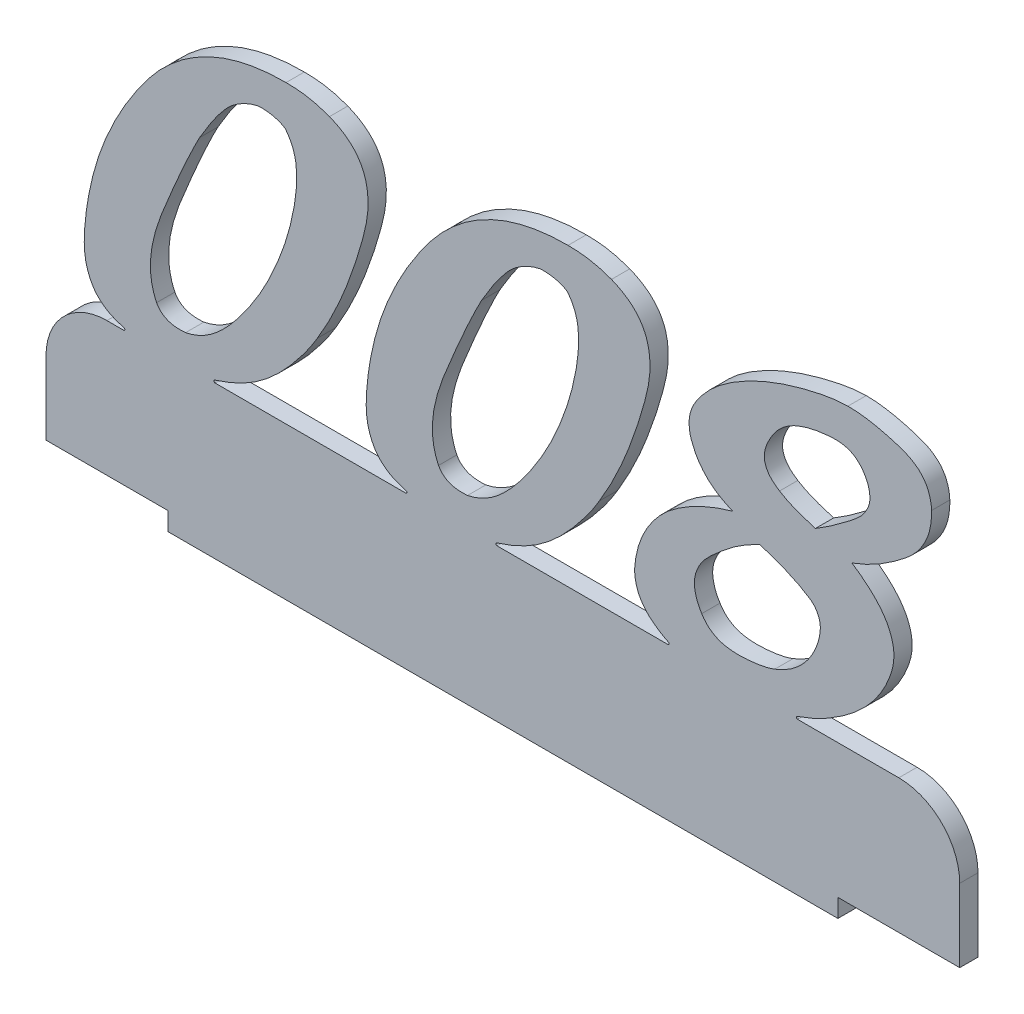
SolidWorks part; units mm, degrees
ref_plane "Front Plane" through (0, 0, 0) normal (0, 0, 1) x (1, 0, 0)
ref_plane "Top Plane" through (0, 0, 0) normal (0, 1, 0) x (1, 0, 0)
ref_plane "Right Plane" through (0, 0, 0) normal (1, 0, 0) x (0, 0, -1)
sketch "Sketch1" plane through (0, 0, 0) normal (0, 0, 1) x (1, 0, 0)
  line L0 (0, 20) -> (150, 20) construction
  line L1 (122.1085, 22) -> (150, 22)
  line L2 (0, 22) -> (0, 0)
  line L3 (0, 0) -> (20, 0)
  line L4 (150, 22) -> (150, 0)
  line L5 (0, 22) -> (14.4385, 22)
  line L6 (26.3356, 22) -> (60.7247, 22)
  line L7 (72.6217, 22) -> (103.0452, 22)
  line L11 (130, 0) -> (150, 0)
  line L13 (20, 0) -> (20, -3)
  line L14 (20, -3) -> (130, -3)
  line L15 (130, 0) -> (130, -3)
  spline S0 degree 3 poles (39.2717, 63.9355) (38.6705, 64.345) (37.2052, 64.8511) (35.6674, 64.9784) (34.8542, 64.9323) knots 0 0 0 0 0.469699 1 1 1 1
  spline S1 degree 3 poles (34.8542, 64.9323) (33.7095, 64.6916) (32.0915, 64.0141) (30.2031, 62.6365) (27.8952, 60.0585) (26.3615, 57.6069) (25.2178, 55.6282) knots 0 0 0 0 0.25259 0.375811 0.50377 1 1 1 1
  spline S2 degree 3 poles (25.2178, 55.6282) (24.7615, 54.8301) (24.1633, 53.5136) (23.2718, 51.6945) (22.5583, 50.113) (21.7939, 48.3937) (20.9934, 46.527) (20.1368, 44.5308) (19.2648, 42.4425) (18.4718, 40.3443) (17.8401, 38.3169) (17.3993, 36.4098) (17.1564, 34.6168) (17.1091, 32.9375) (17.3108, 30.9118) (17.7303, 29.4882) (18.1615, 28.6344) knots 0 0 0 0 0.095871 0.150957 0.21155 0.277044 0.347448 0.42366 0.503899 0.583776 0.657815 0.725493 0.787949 0.846481 0.90051 1 1 1 1
  spline S3 degree 3 poles (18.1615, 28.6344) (18.5199, 27.8914) (20.0194, 26.6841) (21.9323, 26.6676) (22.9113, 26.7384) knots 0 0 0 0 0.446154 1 1 1 1
  spline S4 degree 3 poles (22.9113, 26.7384) (24.3688, 27.0128) (26.5254, 28.0312) (29.0577, 30.199) (31.0082, 32.3562) (32.875, 34.8417) (34.6365, 37.5157) (36.227, 40.3422) (37.6215, 43.2984) (38.8196, 46.3154) (39.8112, 49.3275) (40.5299, 52.316) (41.0344, 55.2066) (41.204, 57.9083) (41.0021, 60.9389) (40.1273, 62.9274) (39.2717, 63.9355) knots 0 0 0 0 0.099523 0.157976 0.224341 0.295662 0.367825 0.440561 0.514606 0.588508 0.65979 0.72866 0.796042 0.857776 0.911265 1 1 1 1
  spline S5 degree 3 poles (14.4385, 22) (13.6581, 22.1621) (12.356, 22.4906) (10.6008, 23.1088) (9.2944, 23.9587) (8.1844, 24.9777) (7.3545, 26.255) (6.749, 27.7265) (6.1954, 30.0914) (6.2651, 32.0111) (6.3554, 33.3256) knots 0.412238 0.412238 0.412238 0.412238 0.501388 0.5623 0.61932 0.674488 0.729675 0.788153 0.851799 1 1 1 1
  spline S6 degree 3 poles (6.3554, 33.3256) (6.5223, 35.5537) (7.0115, 38.8793) (8.1409, 43.2161) (9.2037, 46.4254) (10.5584, 49.5588) (12.0964, 52.6646) (13.9041, 55.7078) (15.9112, 58.6749) (18.1087, 61.4642) (20.583, 63.8831) (23.2252, 65.9707) (26.1055, 67.6181) (29.141, 68.9659) (33.5634, 70.1882) (37.0421, 70.573) (39.4086, 70.5422) knots 0 0 0 0 0.122246 0.183381 0.245051 0.307032 0.370011 0.434579 0.500535 0.565958 0.62848 0.689454 0.749684 0.809559 0.870725 1 1 1 1
  spline S7 degree 3 poles (39.4086, 70.5422) (40.6688, 70.5317) (43.1116, 70.3882) (45.4518, 69.6784) (46.543, 69.2717) knots 0 0 0 0 0.519885 1 1 1 1
  spline S8 degree 3 poles (46.543, 69.2717) (47.8106, 68.7564) (49.6056, 67.763) (51.345, 65.7801) (52.2545, 64.1066) (52.7698, 62.2017) (52.9351, 60.0847) (52.742, 57.7539) (51.9926, 54.4145) (50.714, 50.2481) (48.4129, 43.9445) (46.2159, 39.5182) (44.5493, 36.7658) knots 0 0 0 0 0.111906 0.162582 0.212593 0.265416 0.321766 0.384451 0.454781 0.599581 0.738515 1 1 1 1
  spline S9 degree 3 poles (44.5493, 36.7658) (43.4578, 34.9086) (41.5875, 32.3381) (38.8382, 29.2151) (36.6695, 27.1459) (34.287, 25.3382) (31.6073, 23.8424) (28.9263, 22.7525) (27.1241, 22.2086) (26.3356, 22) knots 0 0 0 0 0.25786 0.380114 0.498337 0.616577 0.737567 0.865048 0.962803 0.962803 0.962803 0.962803
  spline S10 degree 3 poles (85.5579, 63.9355) (84.9566, 64.345) (83.4914, 64.8511) (81.9536, 64.9784) (81.1404, 64.9323) knots 0 0 0 0 0.469699 1 1 1 1
  spline S11 degree 3 poles (81.1404, 64.9323) (79.9957, 64.6916) (78.3776, 64.0141) (76.4893, 62.6365) (74.1814, 60.0585) (72.6477, 57.6069) (71.504, 55.6282) knots 0 0 0 0 0.25259 0.375811 0.50377 1 1 1 1
  spline S12 degree 3 poles (71.504, 55.6282) (71.0477, 54.8301) (70.4495, 53.5136) (69.5579, 51.6945) (68.8445, 50.113) (68.0801, 48.3937) (67.2796, 46.527) (66.423, 44.5308) (65.5509, 42.4425) (64.758, 40.3443) (64.1263, 38.3169) (63.6855, 36.4098) (63.4426, 34.6168) (63.3953, 32.9375) (63.597, 30.9118) (64.0165, 29.4882) (64.4477, 28.6344) knots 0 0 0 0 0.095871 0.150957 0.21155 0.277044 0.347448 0.42366 0.503899 0.583776 0.657815 0.725493 0.787949 0.846481 0.90051 1 1 1 1
  spline S13 degree 3 poles (64.4477, 28.6344) (64.8061, 27.8914) (66.3056, 26.6841) (68.2185, 26.6676) (69.1975, 26.7384) knots 0 0 0 0 0.446154 1 1 1 1
  spline S14 degree 3 poles (69.1975, 26.7384) (70.655, 27.0128) (72.8116, 28.0312) (75.3439, 30.199) (77.2943, 32.3562) (79.1611, 34.8417) (80.9227, 37.5157) (82.5131, 40.3422) (83.9076, 43.2984) (85.1058, 46.3154) (86.0973, 49.3275) (86.816, 52.316) (87.3206, 55.2066) (87.4902, 57.9083) (87.2883, 60.9389) (86.4135, 62.9274) (85.5579, 63.9355) knots 0 0 0 0 0.099523 0.157976 0.224341 0.295662 0.367825 0.440561 0.514606 0.588508 0.65979 0.72866 0.796042 0.857776 0.911265 1 1 1 1
  spline S15 degree 3 poles (60.7247, 22) (59.9443, 22.1621) (58.6422, 22.4906) (56.8869, 23.1088) (55.5805, 23.9587) (54.4706, 24.9777) (53.6407, 26.255) (53.0352, 27.7265) (52.4816, 30.0914) (52.5512, 32.0111) (52.6416, 33.3256) knots 0.412238 0.412238 0.412238 0.412238 0.501388 0.5623 0.61932 0.674488 0.729675 0.788153 0.851799 1 1 1 1
  spline S16 degree 3 poles (52.6416, 33.3256) (52.8085, 35.5537) (53.2977, 38.8793) (54.4271, 43.2161) (55.4899, 46.4254) (56.8445, 49.5588) (58.3825, 52.6646) (60.1903, 55.7078) (62.1973, 58.6749) (64.3949, 61.4642) (66.8691, 63.8831) (69.5114, 65.9707) (72.3916, 67.6181) (75.4271, 68.9659) (79.8495, 70.1882) (83.3282, 70.573) (85.6947, 70.5422) knots 0 0 0 0 0.122246 0.183381 0.245051 0.307032 0.370011 0.434579 0.500535 0.565958 0.62848 0.689454 0.749684 0.809559 0.870725 1 1 1 1
  spline S17 degree 3 poles (85.6947, 70.5422) (86.955, 70.5317) (89.3978, 70.3882) (91.738, 69.6784) (92.8292, 69.2717) knots 0 0 0 0 0.519885 1 1 1 1
  spline S18 degree 3 poles (92.8292, 69.2717) (94.0968, 68.7564) (95.8918, 67.763) (97.6311, 65.7801) (98.5406, 64.1066) (99.0559, 62.2017) (99.2212, 60.0847) (99.0281, 57.7539) (98.2787, 54.4145) (97.0002, 50.2481) (94.699, 43.9445) (92.5021, 39.5182) (90.8355, 36.7658) knots 0 0 0 0 0.111906 0.162582 0.212593 0.265416 0.321766 0.384451 0.454781 0.599581 0.738515 1 1 1 1
  spline S19 degree 3 poles (90.8355, 36.7658) (89.744, 34.9086) (87.8737, 32.3381) (85.1243, 29.2151) (82.9556, 27.1459) (80.5732, 25.3382) (77.8935, 23.8424) (75.2124, 22.7525) (73.4103, 22.2086) (72.6217, 22) knots 0 0 0 0 0.25786 0.380114 0.498337 0.616577 0.737567 0.865048 0.962803 0.962803 0.962803 0.962803
  spline S20 degree 3 poles (126.371, 33.6579) (126.7031, 34.3779) (127.007, 35.4664) (127.1499, 36.897) (127.036, 37.826) (126.7259, 38.6623) (126.2545, 39.4218) (125.5719, 40.0681) (122.7145, 41.8666) (119.7983, 42.9292) (117.2037, 43.7439) knots 0 0 0 0 0.146792 0.208761 0.266158 0.319044 0.373489 0.430886 0.492033 1 1 1 1
  spline S21 degree 3 poles (117.2037, 43.7439) (115.8329, 43.1378) (113.7552, 41.957) (111.129, 39.9001) (109.3812, 38.3904) (108.0765, 37.0582) (107.3169, 35.9836) (106.7801, 34.8893) (106.4729, 33.7682) (106.4123, 32.6281) (106.6797, 31.0316) (107.1772, 29.8802) (107.6455, 29.1622) knots 0 0 0 0 0.226027 0.358515 0.502651 0.57426 0.639155 0.700254 0.757231 0.813328 0.871012 1 1 1 1
  spline S22 degree 3 poles (107.6455, 29.1622) (108.1724, 28.2784) (109.3642, 27.149) (111.4463, 26.4719) (113.1918, 26.2848) (114.9735, 26.3447) (117.1543, 26.5625) (118.703, 26.9037) (119.647, 27.2662) knots 0 0 0 0 0.236244 0.35975 0.496904 0.637588 0.76846 1 1 1 1
  spline S23 degree 3 poles (119.647, 27.2662) (121.1515, 27.8316) (123.9411, 29.5094) (125.7854, 32.1967) (126.371, 33.6579) knots 0 0 0 0 0.505931 1 1 1 1
  spline S24 degree 3 poles (134.6197, 61.8831) (134.1441, 62.8535) (133.0166, 64.1788) (130.8548, 64.8904) (129.0886, 64.9329) (127.3209, 64.7401) (125.1822, 64.3905) (123.7099, 63.876) (122.8136, 63.4663) knots 0 0 0 0 0.248439 0.370849 0.507489 0.647531 0.775536 1 1 1 1
  spline S25 degree 3 poles (122.8136, 63.4663) (121.8418, 63.0051) (120.4732, 62.0297) (119.1401, 60.2091) (118.4508, 58.9131) (118.0456, 57.81) (117.9045, 56.9963) (117.9117, 56.2139) (118.124, 55.4799) (118.4593, 54.7795) (119.1643, 53.8592) (119.908, 53.3314) (120.4289, 52.9894) knots 0 0 0 0 0.241285 0.367348 0.502442 0.568888 0.629575 0.686496 0.742418 0.79919 0.859595 1 1 1 1
  spline S26 degree 3 poles (120.4289, 52.9894) (121.2124, 52.4755) (123.1493, 51.592) (125.1633, 50.9151) (126.3124, 50.6047) knots 0 0 0 0 0.439761 1 1 1 1
  spline S27 degree 3 poles (126.3124, 50.6047) (127.2787, 51.1657) (128.7891, 52.1534) (130.8652, 53.6905) (132.3575, 54.7995) (133.5146, 55.8002) (134.234, 56.5989) (134.7471, 57.4396) (135.118, 58.2832) (135.2814, 59.1669) (135.2035, 60.4022) (134.9415, 61.3163) (134.6197, 61.8831) knots 0 0 0 0 0.215363 0.347509 0.497992 0.573615 0.642147 0.70419 0.76274 0.818912 0.875489 1 1 1 1
  spline S28 degree 3 poles (128.4234, 24.686) (126.6145, 23.6397) (124.4927, 22.7447) (122.3049, 22.0597) (122.1085, 22) knots 0 0 0 0 0.235486 0.258652 0.258652 0.258652 0.258652
  spline S29 degree 3 poles (102.8175, 22.1059) (101.7572, 22.524) (100.3507, 23.3543) (98.7375, 24.6924) (97.8545, 25.7801) (97.1816, 26.9581) (96.7799, 28.2371) (96.5898, 29.6075) (96.7344, 31.5138) (97.2465, 33.8805) (98.8137, 37.4794) (100.7091, 39.7807) (102.2311, 41.0465) knots 0 0 0 0 0.145412 0.20817 0.267501 0.323943 0.380975 0.438244 0.500118 0.624909 0.746818 1 1 1 1
  spline S30 degree 3 poles (102.2311, 41.0465) (103.6714, 42.2408) (107.0399, 44.3128) (110.7342, 45.7155) (112.7276, 46.2654) knots 0 0 0 0 0.474551 1 1 1 1
  spline S31 degree 3 poles (112.7276, 46.2654) (111.5693, 46.7604) (109.4237, 47.856) (107.789, 49.6262) (107.1764, 50.5461) knots 0 0 0 0 0.533807 1 1 1 1
  spline S32 degree 3 poles (107.1764, 50.5461) (106.7046, 51.2173) (106.2029, 52.2827) (105.6931, 53.7287) (105.579, 54.7709) (105.5582, 55.7857) (105.7477, 56.7753) (106.0821, 57.744) (106.7544, 59.0036) (107.8684, 60.484) (109.4356, 62.1654) (111.3093, 63.6824) (113.4262, 65.0561) (115.7098, 66.3096) (118.1238, 67.4331) (120.6456, 68.3777) (123.1966, 69.189) (125.6625, 69.8089) (128.4511, 70.4124) (130.4282, 70.6418) (131.6486, 70.6595) knots 0 0 0 0 0.065493 0.094654 0.122662 0.149381 0.175998 0.203171 0.231525 0.29042 0.351574 0.415972 0.483686 0.554266 0.62529 0.697586 0.770658 0.840418 0.901966 1 1 1 1
  spline S33 degree 3 poles (131.6486, 70.6595) (133.0211, 70.6668) (135.1475, 70.418) (138.0257, 69.7443) (139.9411, 69.1958) (141.4472, 68.6239) (142.4536, 68.0724) (143.3248, 67.4298) (144.0421, 66.6772) (144.6021, 65.8144) (145.153, 64.5008) (145.3565, 63.4237) (145.3703, 62.6845) knots 0 0 0 0 0.233892 0.363936 0.504338 0.573731 0.638438 0.699607 0.757824 0.814893 0.874183 1 1 1 1
  spline S34 degree 3 poles (145.3703, 62.6845) (145.3913, 61.8265) (145.2887, 60.554) (144.8716, 58.9239) (144.3943, 57.7845) (143.7781, 56.7001) (143.0409, 55.6627) (142.1414, 54.692) (140.7766, 53.5044) (138.9709, 52.1735) (136.1161, 50.3066) (133.8395, 49.2533) (132.3132, 48.6892) knots 0 0 0 0 0.125844 0.186121 0.246118 0.306464 0.368798 0.432388 0.500096 0.633912 0.761177 1 1 1 1
  spline S35 degree 3 poles (132.3132, 48.6892) (133.6167, 47.8278) (135.401, 46.4512) (137.2988, 44.3202) (138.2903, 42.7422) (138.9251, 41.1237) (139.2356, 39.4701) (139.1697, 37.7766) (138.739, 36.0943) (138.063, 34.4412) (137.2198, 32.8297) (136.1999, 31.2835) (135.0018, 29.8033) (133.5981, 28.4273) (131.4899, 26.5888) (129.6705, 25.4411) (128.4234, 24.686) knots 0 0 0 0 0.151287 0.216506 0.275096 0.330574 0.383733 0.436709 0.493116 0.550815 0.609171 0.66878 0.729711 0.792995 0.85869 1 1 1 1
  spline S36 degree 2 poles (103.0452, 22) (102.931, 22.052) (102.8175, 22.1059) knots 0.990597 0.990597 0.990597 1 1 1
  dimension "D1" = 150
  dimension "D2" = 3
  dimension "D3" = 20
  dimension "D4" = 20
  dimension "D5" = 20
extrude "Boss-Extrude1" add sketch "Sketch1" along normal blind 3
fillet "Fillet1" radius 10 2 edges at (0, 22, 1.5) (150, 22, 1.5)
fillet "Fillet2" radius 0.2 6 edges at (26.3356, 22, 1.5) (72.6217, 22, 1.5) (122.1085, 22, 1.5) (103.0452, 22, 1.5) (60.7247, 22, 1.5) (14.4385, 22, 1.5)
